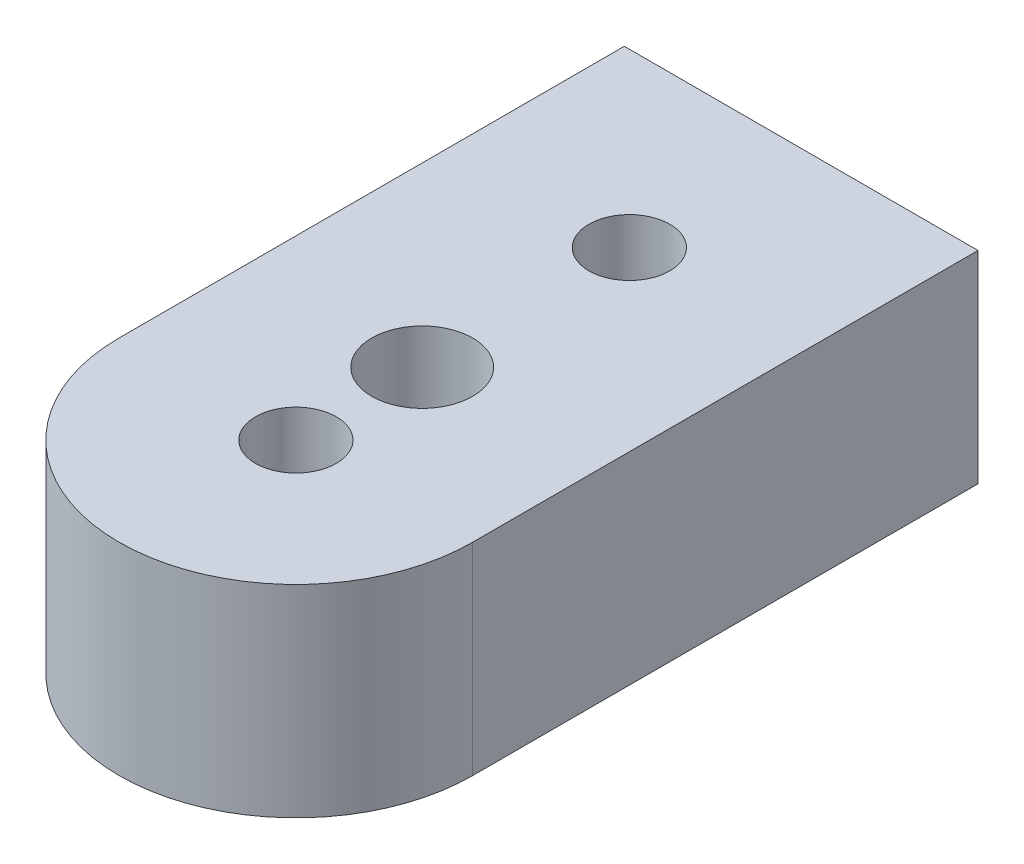
SolidWorks part; units mm, degrees
material "1.5714 (16NiCr4)"
ref_plane "Front Plane" through (0, 0, 0) normal (0, 0, 1) x (1, 0, 0)
ref_plane "Top Plane" through (0, 0, 0) normal (0, 1, 0) x (1, 0, 0)
ref_plane "Right Plane" through (0, 0, 0) normal (1, 0, 0) x (0, 0, -1)
sketch "Sketch1" plane through (0, 0, 0) normal (0, 1, 0) x (1, 0, 0)
  line L0 (0, 311.2411) -> (0, -141.2221) construction
  line L1 (-7, 15) -> (7, 15)
  line L2 (7, 15) -> (7, -5)
  line L3 (-7, -5) -> (-7, 15)
  arc A0 (7, -5) -> (-7, -5) centre (0, -5) cw
  circle A3 centre (0, -5) radius 1.6
  circle A4 centre (0, 8.2) radius 1.6
  circle A5 centre (0, 0) radius 2
  point P19 (0, 15)
  dimension "D1" = 3.2
  dimension "D4" = 3.2
  dimension "D6" = 4
  dimension "D2" = 14
  dimension "D3" = 13.2
  dimension "D5" = 27
  dimension "D7" = 15
extrude "Boss-Extrude1" add sketch "Sketch1" along normal blind 8
equation "\"D4@Sketch1\"=\"D1@Sketch1\""
